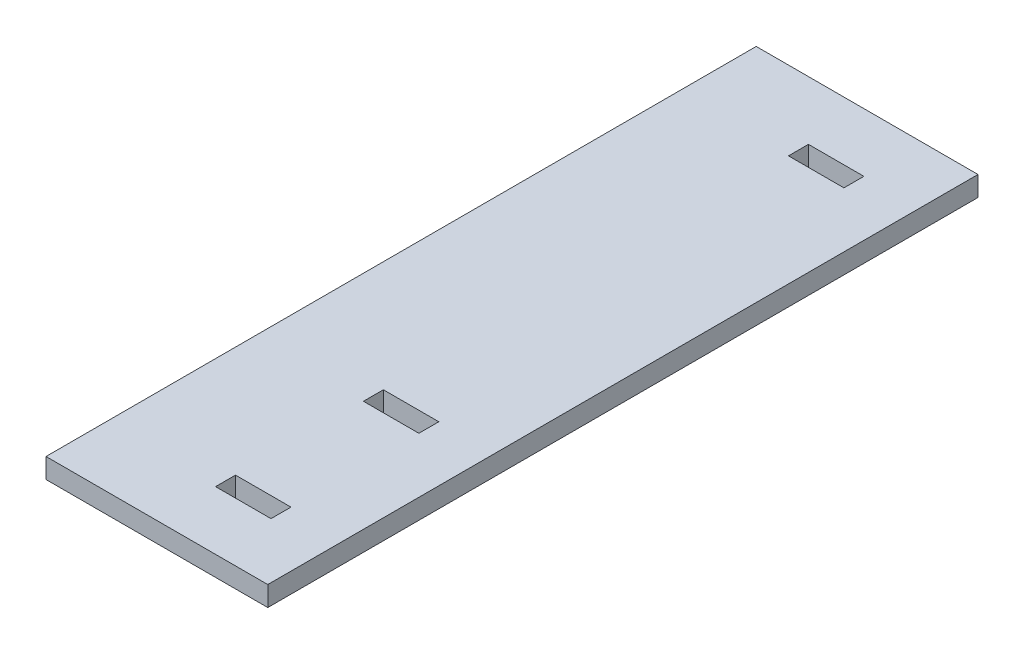
SolidWorks part; units mm, degrees
ref_plane "Front Plane" through (0, 0, 0) normal (0, 0, 1) x (1, 0, 0)
ref_plane "Top Plane" through (0, 0, 0) normal (0, 1, 0) x (1, 0, 0)
ref_plane "Right Plane" through (0, 0, 0) normal (1, 0, 0) x (0, 0, -1)
sketch "Sketch1" plane through (0, 0, 0) normal (0, 1, 0) x (1, 0, 0)
  line L0 (-60, 66.7875) -> (-30, 66.7875)
  line L1 (-60, -29.2875) -> (-30, -29.2875)
  line L2 (-60, -29.2875) -> (-60, 66.7875)
  line L3 (-45, -18.65) -> (-60, -18.65) construction
  line L4 (-30, 66.7875) -> (-30, -29.2875)
  line L5 (-37.5, 1.35) -> (-45, 1.35)
  line L6 (-37.5, 1.35) -> (-37.5, -1.35)
  line L7 (-37.5, -1.35) -> (-45, -1.35)
  line L8 (-45, 1.35) -> (-45, -1.35)
  line L9 (-37.5, 56.15) -> (-45, 56.15)
  line L10 (-37.5, 56.15) -> (-37.5, 58.85)
  line L11 (-37.5, 58.85) -> (-45, 58.85)
  line L12 (-45, 56.15) -> (-45, 58.85)
  line L13 (-37.5, -18.65) -> (-45, -18.65)
  line L14 (-37.5, -18.65) -> (-37.5, -21.35)
  line L15 (-37.5, -21.35) -> (-45, -21.35)
  line L16 (-45, -18.65) -> (-45, -21.35)
  line L17 (-30, -30) -> (-30, 70) construction
  line L18 (-37.5, -18.65) -> (-30, -18.65) construction
  point P18 (-37.5, 0)
  point P19 (-37.5, -20)
  point P20 (-37.5, 57.5)
  dimension "D1" = 30
  dimension "D2" = 7.9375
  dimension "D3" = 2.7
  dimension "D4" = 45
  dimension "D5" = 7.5
  dimension "D6" = 20
  dimension "D7" = 57.5
  dimension "D8" = 7.9375
extrude "Base" add sketch "Sketch1" along normal blind 2.7
